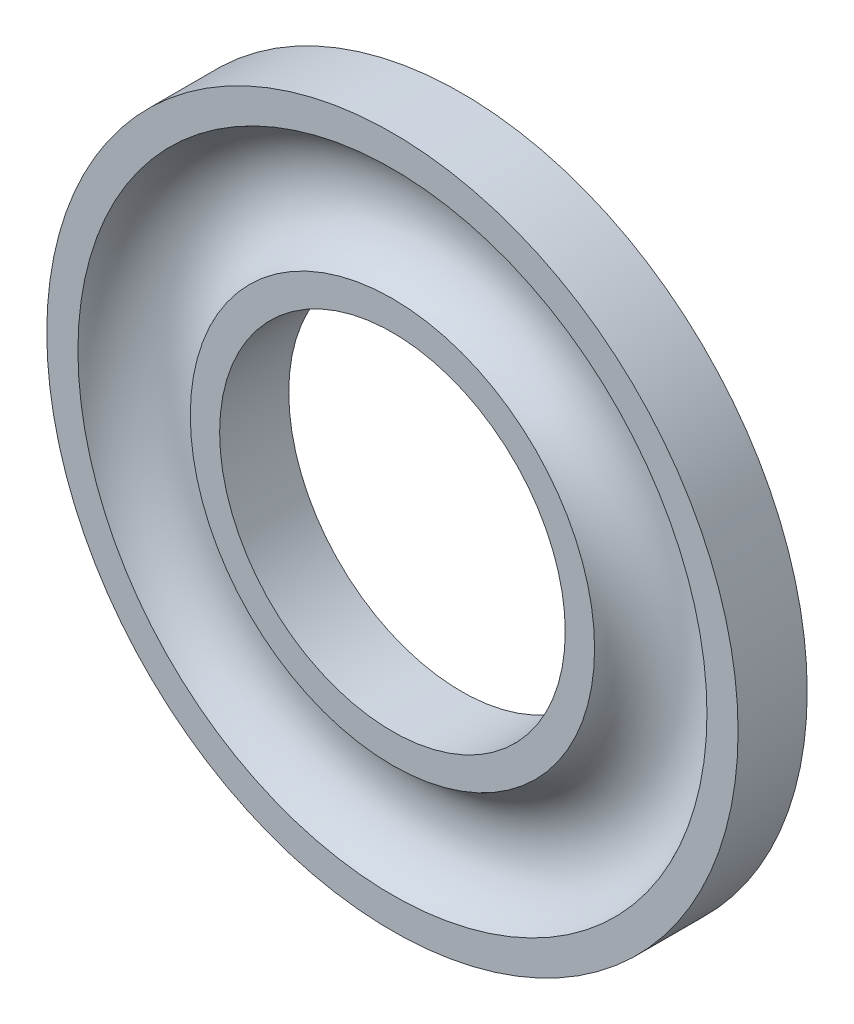
SolidWorks part; units mm, degrees
ref_plane "Спереди" through (0, 0, 0) normal (0, 0, 1) x (1, 0, 0)
ref_plane "Сверху" through (0, 0, 0) normal (0, 1, 0) x (1, 0, 0)
ref_plane "Справа" through (0, 0, 0) normal (1, 0, 0) x (0, 0, -1)
sketch "Эскиз1" plane through (0, 0, 0) normal (0, 0, 1) x (1, 0, 0)
  circle A0 centre (0, 0) radius 10
  circle A1 centre (0, 0) radius 20
  dimension "D1" = 20
  dimension "D2" = 40
extrude "Вытянуть1" add sketch "Эскиз1" along normal blind 4
sketch "Эскиз2" plane through (0, 0, 4) normal (0, 0, 1) x (1, 0, 0)
  circle A0 centre (0, 0) radius 15
  circle A1 centre (0, 0) radius 10 construction
  dimension "D1" = 30
sketch "Эскиз3" plane through (0, 0, 0) normal (0, 1, 0) x (1, 0, 0)
  circle A0 centre (14.9478, -5.295) radius 3.5
  dimension "D1" = 7
  dimension "D2" = 14.9478
  dimension "D3" = 5.295
sweep "Вырез-По траектории1" cut profiles "Эскиз3" path "Эскиз2"
